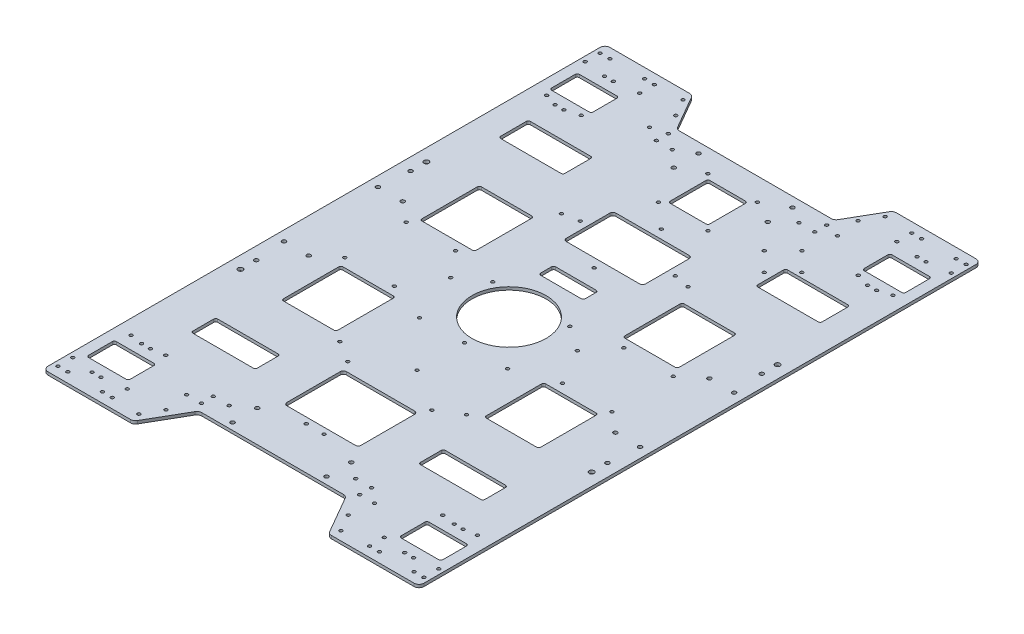
SolidWorks part; units mm, degrees
material "Hexcel AS4C (3000 丝)"
ref_plane "前视基准面" through (0, 0, 0) normal (0, 0, 1) x (1, 0, 0)
ref_plane "上视基准面" through (0, 0, 0) normal (0, 1, 0) x (1, 0, 0)
ref_plane "右视基准面" through (0, 0, 0) normal (1, 0, 0) x (0, 0, -1)
sketch "草图1" plane through (0, 0, 0) normal (0, 1, 0) x (1, 0, 0)
  line L0 (0, 420.0815) -> (0, -400.8011) construction
  line L1 (190, 287) -> (101.545, 287)
  line L2 (190, 287) -> (190, 0)
  line L3 (190, -281) -> (144.0917, -281)
  line L4 (-190, 287) -> (-190, 0)
  line L5 (-313.6361, 0) -> (397.123, 0) construction
  line L6 (144.0917, -281) -> (98.6603, -281)
  line L7 (-101.545, 287) -> (-79.6057, 249)
  line L8 (-79.6057, 249) -> (79.6057, 249)
  line L9 (79.6057, 249) -> (101.545, 287)
  line L10 (-98.6603, -281) -> (-74.4115, -239)
  line L12 (-74.4115, -239) -> (74.4115, -239)
  line L13 (-144.0917, -281) -> (-190, -281)
  line L14 (-101.545, 287) -> (-190, 287)
  line L15 (-98.6603, -281) -> (-144.0917, -281)
  line L17 (190, 0) -> (190, -281)
  line L20 (190, 287) -> (190, -281) construction
  line L22 (74.4115, -239) -> (98.6603, -281)
  line L24 (-190, 0) -> (-190, -281)
  line L26 (-190, 287) -> (-190, -281) construction
  line L44 (229.3448, 326.3448) -> (229.3448, -320.3448) construction
  line L45 (-229.3448, 326.3448) -> (-229.3448, -320.3448) construction
  line L46 (-78.8293, 326.3448) -> (-229.3448, 326.3448) construction
  line L47 (-78.8293, 326.3448) -> (-56.89, 288.3448) construction
  line L48 (-56.89, 288.3448) -> (56.89, 288.3448) construction
  line L49 (56.89, 288.3448) -> (78.8293, 326.3448) construction
  line L50 (229.3448, 326.3448) -> (78.8293, 326.3448) construction
  line L51 (-121.376, -320.3448) -> (-229.3448, -320.3448) construction
  line L52 (229.3448, -320.3448) -> (121.376, -320.3448) construction
  line L53 (-98.6603, -281) -> (-121.376, -320.3448) construction
  line L54 (98.6603, -281) -> (121.376, -320.3448) construction
  line L55 (-132.7338, -261.3276) -> (-144.0917, -281) construction
  line L56 (-132.7338, -261.3276) -> (-97.1273, -199.6552) construction
  line L57 (-97.1273, -199.6552) -> (97.1273, -199.6552) construction
  line L58 (97.1273, -199.6552) -> (132.7338, -261.3276) construction
  line L59 (132.7338, -261.3276) -> (144.0917, -281) construction
  point P0 (0, 0)
  point P10 (-110.2073, -274)
  point P13 (-79.8964, -221.5)
  point P14 (79.8964, -221.5)
  point P16 (110.2073, -274)
  point P21 (200, -271.5)
  point P22 (200, 291.5)
  point P23 (-145.7725, 287)
  point P24 (77.0076, 246.5)
  point P25 (-77.0076, 246.5)
  point P27 (-200, 291.5)
  point P28 (-200, -271.5)
  dimension "D1" = 568
  dimension "D2" = 380
  dimension "D3" = 38
  dimension "D4" = 197.3205
  dimension "D5" = 120
  dimension "D6" = 60
  dimension "D7" = 203.09
  dimension "D8" = 42
  dimension "D9" = 287
extrude "基本板" add sketch "草图1" along normal blind 3
sketch "草图2" plane through (0, 3, 0) normal (0, 1, 0) x (1, 0, 0)
  circle A0 centre (0, 0) radius 37.5
  circle A1 centre (38.9711, 22.5) radius 1.6
  circle A3 centre (0, 0) radius 37.5
  circle A5 centre (0, -45) radius 1.6
  circle A6 centre (0, 0) radius 37.5
  circle A7 centre (-38.9711, 22.5) radius 1.6
  point P14 (0, 0)
  point P16 (0, 0)
  dimension "D1" = 75
  dimension "D3" = 3.2
  dimension "D2" = 45
  dimension "D4" = 3
extrude "云台孔" cut sketch "草图2" against normal blind 3 contours A1 | A0 | A5 | A7
sketch "草图8" plane through (0, 3, 0) normal (0, 1, 0) x (1, 0, 0)
  line L0 (0, 320.5112) -> (0, -345.0597) construction
  line L13 (82.5, -149) -> (147.5, -149)
  line L14 (-82.5, -149) -> (-147.5, -149)
  line L15 (-82.5, -149) -> (-82.5, -174)
  line L16 (-82.5, -174) -> (-147.5, -174)
  line L17 (-147.5, -149) -> (-147.5, -174)
  line L18 (-82.5, -149) -> (-147.5, -174) construction
  line L19 (-82.5, -174) -> (-147.5, -149) construction
  line L20 (147.5, -149) -> (147.5, -174)
  line L21 (82.5, -149) -> (147.5, -174) construction
  line L22 (82.5, -174) -> (147.5, -149) construction
  line L23 (82.5, -149) -> (82.5, -174)
  line L24 (82.5, -174) -> (147.5, -174)
  point P12 (-115, -161.5)
  dimension "D1" = 230
  dimension "D5" = 174
  dimension "D7" = 25
  dimension "D8" = 65
extrude "减重过线孔" cut sketch "草图8" against normal blind 3
sketch "草图41" plane through (0, 3, 0) normal (0, 1, 0) x (1, 0, 0)
  line L0 (0, 188.4867) -> (0, -152.142) construction
  line L1 (-206.7892, 0) -> (229.7274, 0) construction
  line L2 (-130, 100) -> (-75, 100)
  line L3 (-130, 100) -> (-130, 40)
  line L4 (-130, 40) -> (-75, 40)
  line L5 (-75, 100) -> (-75, 40)
  line L6 (75, 100) -> (75, 40)
  line L7 (130, 40) -> (75, 40)
  line L8 (130, 100) -> (130, 40)
  line L9 (130, 100) -> (75, 100)
  line L10 (130, -100) -> (75, -100)
  line L11 (130, -100) -> (130, -40)
  line L12 (130, -40) -> (75, -40)
  line L13 (75, -100) -> (75, -40)
  line L14 (-75, -100) -> (-75, -40)
  line L15 (-130, -40) -> (-75, -40)
  line L16 (-130, -100) -> (-130, -40)
  line L17 (-130, -100) -> (-75, -100)
  dimension "D1" = 40
  dimension "D2" = 75
  dimension "D3" = 55
  dimension "D4" = 60
extrude "减重过线孔2" cut sketch "草图41" against normal blind 10
sketch "草图10" plane through (0, 3, 0) normal (0, 1, 0) x (1, 0, 0)
  line L0 (0, 320.3944) -> (0, -95.0551) construction
  line L1 (-162.5, 182) -> (-97.5, 182)
  line L2 (-162.5, 182) -> (-162.5, 152)
  line L3 (-162.5, 152) -> (-97.5, 152)
  line L4 (-97.5, 182) -> (-97.5, 152)
  line L5 (-162.5, 182) -> (-97.5, 152) construction
  line L6 (-162.5, 152) -> (-97.5, 182) construction
  line L7 (162.5, 152) -> (97.5, 152)
  line L8 (97.5, 152) -> (97.5, 182)
  line L9 (97.5, 182) -> (162.5, 182)
  line L11 (162.5, 182) -> (162.5, 152)
  point P0 (-130, 167)
  dimension "D1" = 65
  dimension "D2" = 30
  dimension "D3" = 167
  dimension "D4" = 130
  dimension "D5" = 65
extrude "后电机过线孔" cut sketch "草图10" against normal blind 3
sketch "草图11" plane through (0, 3, 0) normal (0, 1, 0) x (1, 0, 0)
  line L0 (-190, 287) -> (-190, -281) construction
  line L1 (-179, 248) -> (-137, 248)
  line L2 (-179, 248) -> (-179, 220)
  line L3 (-179, 220) -> (-137, 220)
  line L4 (-137, 248) -> (-137, 220)
  line L5 (-179, 248) -> (-137, 220) construction
  line L6 (-179, 220) -> (-137, 248) construction
  line L8 (-158, 274.32) -> (-158, 185.5546) construction
  line L9 (-208.9066, 234) -> (-106.7696, 234) construction
  line L10 (-264.4169, 0) -> (335.6364, 0) construction
  line L11 (0, 360.1922) -> (0, -386.7193) construction
  line L12 (179, 248) -> (179, 220)
  line L13 (179, 220) -> (137, 220)
  line L14 (137, 248) -> (137, 220)
  line L15 (179, 248) -> (137, 248)
  line L16 (179, -248) -> (137, -248)
  line L17 (137, -248) -> (137, -220)
  line L18 (179, -220) -> (137, -220)
  line L19 (179, -248) -> (179, -220)
  line L20 (-179, -248) -> (-179, -220)
  line L21 (-179, -220) -> (-137, -220)
  line L22 (-137, -248) -> (-137, -220)
  line L23 (-179, -248) -> (-137, -248)
  circle A0 centre (-153.5, 259) radius 1.6
  circle A1 centre (-162.5, 259) radius 1.6
  circle A2 centre (-153.5, 209) radius 1.6
  circle A3 centre (-162.5, 209) radius 1.6
  circle A4 centre (153.5, 259) radius 1.6
  circle A5 centre (162.5, 259) radius 1.6
  circle A6 centre (153.5, 209) radius 1.6
  circle A7 centre (162.5, 209) radius 1.6
  circle A8 centre (162.5, -209) radius 1.6
  circle A9 centre (153.5, -209) radius 1.6
  circle A10 centre (162.5, -259) radius 1.6
  circle A11 centre (153.5, -259) radius 1.6
  circle A12 centre (-162.5, -209) radius 1.6
  circle A13 centre (-153.5, -209) radius 1.6
  circle A14 centre (-153.5, -259) radius 1.6
  circle A15 centre (-162.5, -259) radius 1.6
  point P0 (-158, 234)
  dimension "D5" = 3.2
  dimension "D1" = 42
  dimension "D2" = 28
  dimension "D3" = 32
  dimension "D4" = 468
  dimension "D6" = 4.5
  dimension "D7" = 25
extrude "悬挂过孔" cut sketch "草图11" against normal blind 3
sketch "草图13" plane through (0, 3, 0) normal (0, 1, 0) x (1, 0, 0)
  line L0 (79.6057, 249) -> (-79.6057, 249) construction
  line L1 (25, 226) -> (-25, 226) construction
  line L2 (25, 226) -> (25, 176) construction
  line L3 (25, 176) -> (-25, 176) construction
  line L4 (-25, 226) -> (-25, 176) construction
  line L5 (25, 226) -> (-25, 176) construction
  line L6 (25, 176) -> (-25, 226) construction
  circle A0 centre (25, 176) radius 1.6
  circle A1 centre (25, 226) radius 1.6
  circle A2 centre (-25, 226) radius 1.6
  circle A3 centre (-25, 176) radius 1.6
  point P0 (0, 201)
  dimension "D1" = 3.2
  dimension "D2" = 50
  dimension "D3" = 48
  dimension "D4" = 50
extrude "原灯柱固定孔" cut sketch "草图13" against normal blind 3
sketch "草图14" plane through (0, 3, 0) normal (0, 1, 0) x (1, 0, 0)
  line L0 (0, 388.2914) -> (0, -299.2561) construction
  line L1 (79.6057, 249) -> (-79.6057, 249) construction
  line L4 (-74.4115, -239) -> (74.4115, -239) construction
  circle A0 centre (-47.5, 239) radius 2
  circle A1 centre (-47.5, 214) radius 2
  circle A2 centre (47.5, 214) radius 2
  circle A3 centre (47.5, 239) radius 2
  circle A4 centre (-47.5, -207) radius 2
  circle A5 centre (-47.5, -232) radius 2
  circle A6 centre (47.5, -232) radius 2
  circle A7 centre (47.5, -207) radius 2
  dimension "D1" = 25
  dimension "D3" = 4
  dimension "D4" = 4
  dimension "D6" = 4
  dimension "D7" = 4
  dimension "D2" = 10
  dimension "D5" = 47.5
  dimension "D8" = 25
  dimension "D9" = 7
  dimension "D10" = 95
extrude "前后装甲板固定孔" cut sketch "草图14" against normal blind 3
sketch "草图15" plane through (0, 3, 0) normal (0, 1, 0) x (1, 0, 0)
  line L0 (-212.3646, 0) -> (277.5556, 0) construction
  line L1 (190, -281) -> (190, 287) construction
  line L2 (0, 389.4336) -> (0, -385.931) construction
  circle A0 centre (155, 47.5) radius 2
  circle A1 centre (180, 47.5) radius 2
  circle A2 centre (180, -47.5) radius 2
  circle A3 centre (155, -47.5) radius 2
  circle A4 centre (-155, -47.5) radius 2
  circle A5 centre (-180, -47.5) radius 2
  circle A6 centre (-180, 47.5) radius 2
  circle A7 centre (-155, 47.5) radius 2
  dimension "D1" = 25
  dimension "D4" = 4
  dimension "D5" = 4
  dimension "D2" = 10
  dimension "D3" = 47.5
extrude "左右装甲板固定孔" cut sketch "草图15" against normal blind 3
sketch "草图16" plane through (0, 3, 0) normal (0, 1, 0) x (1, 0, 0)
  line L0 (0, 371.6115) -> (0, -351.9198) construction
  line L1 (79.6057, 249) -> (-79.6057, 249) construction
  line L2 (-74.4115, -239) -> (74.4115, -239) construction
  circle A0 centre (-64, 229) radius 1.6
  circle A1 centre (-64, 117) radius 1.6
  circle A2 centre (-64, 5) radius 1.6
  circle A3 centre (-64, -107) radius 1.6
  circle A4 centre (-64, -219) radius 1.6
  circle A5 centre (64, 229) radius 1.6
  circle A6 centre (64, -107) radius 1.6
  circle A7 centre (64, 5) radius 1.6
  circle A8 centre (64, 117) radius 1.6
  circle A9 centre (64, -219) radius 1.6
  dimension "D1" = 20
  dimension "D2" = 3.2
  dimension "D3" = 128
  dimension "D4" = 20
  dimension "D5" = 4
  dimension "D6" = 112
  dimension "D7" = 112
extrude "加强筋固定孔" cut sketch "草图16" against normal blind 3
sketch "草图17" plane through (0, 3, 0) normal (0, 1, 0) x (1, 0, 0)
  line L0 (134.2077, 331.9193) -> (53.2432, 191.6847) construction
  line L1 (101.545, 287) -> (79.6057, 249) construction
  line L2 (190, 287) -> (101.545, 287) construction
  line L3 (0, 408.349) -> (0, -455.0242) construction
  line L4 (-45.0771, -171.5407) -> (-117.5498, -297.067) construction
  line L5 (190, -281) -> (190, 287) construction
  line L6 (-190, -281) -> (-98.6603, -281) construction
  line L7 (-190, 287) -> (-190, -281) construction
  line L8 (-98.6603, -281) -> (-74.4115, -239) construction
  circle A0 centre (95, 264.0096) radius 1.6
  circle A1 centre (102.5, 277) radius 1.6
  circle A3 centre (-95, -258.0096) radius 1.6
  circle A4 centre (-102.5, -271) radius 1.6
  circle A7 centre (102.5, -271) radius 1.6
  circle A8 centre (95, -258.0096) radius 1.6
  circle A10 centre (-102.5, 277) radius 1.6
  circle A11 centre (-95, 264.0096) radius 1.6
  dimension "D2" = 15
  dimension "D4" = 3.2
  dimension "D5" = 3.2
  dimension "D6" = 95
  dimension "D11" = 3.2
  dimension "D12" = 3.2
  dimension "D3" = 95
  dimension "D8" = 10
  dimension "D14" = 10
  dimension "D16" = 15
extrude "前后挡片固定孔" [suppressed] cut sketch "草图17" against normal blind 3
sketch "草图18" plane through (0, 3, 0) normal (0, 1, 0) x (1, 0, 0)
  line L0 (325.6997, 0) -> (-414.0484, 0) construction
  line L1 (167.6795, 77.7768) -> (228.1621, 112.6965) construction
  line L2 (190, -281) -> (190, 287) construction
  line L3 (0, 334.7186) -> (0, -324.7689) construction
  line L4 (190, -281) -> (190, 287) construction
  circle A0 centre (167.6795, 77.7768) radius 1.6
  circle A1 centre (185, 87.7768) radius 1.6
  circle A2 centre (185, -87.7768) radius 1.6
  circle A3 centre (167.6795, -77.7768) radius 1.6
  circle A4 centre (-167.6795, -77.7768) radius 1.6
  circle A5 centre (-185, -87.7768) radius 1.6
  circle A6 centre (-185, 87.7768) radius 1.6
  circle A7 centre (-167.6795, 77.7768) radius 1.6
  point P24 (190, 90.6636)
  dimension "D1" = 30
  dimension "D5" = 3.2
  dimension "D6" = 3.2
  dimension "D2" = 181.3272
  dimension "D3" = 20
  dimension "D4" = 5
extrude "左右挡片固定孔" [suppressed] cut sketch "草图18" against normal blind 3
sketch "草图19" plane through (0, 3, 0) normal (0, 1, 0) x (1, 0, 0)
  line L0 (-190, 287) -> (-190, -281) construction
  line L2 (0, 300.5357) -> (0, -347.8075) construction
  line L3 (-284.3527, 0) -> (241.9977, 0) construction
  circle A0 centre (-177.5, -78) radius 2
  circle A1 centre (-177.5, -94) radius 2.5
  circle A2 centre (-177.5, 94) radius 2.5
  circle A3 centre (-177.5, 78) radius 2
  circle A4 centre (177.5, -94) radius 2.5
  circle A5 centre (177.5, -78) radius 2
  circle A6 centre (177.5, 78) radius 2
  circle A7 centre (177.5, 94) radius 2.5
  dimension "D1" = 12.5
  dimension "D3" = 4
  dimension "D4" = 5
  dimension "D2" = 188
  dimension "D5" = 16
extrude "纵车架固定孔" cut sketch "草图19" against normal blind 3
sketch "草图21" plane through (0, 3, 0) normal (0, 1, 0) x (1, 0, 0)
  line L1 (-84.0108, 0) -> (121.9234, 0) construction
  circle A0 centre (0, -93) radius 1.6
  dimension "D1" = 186
  dimension "D2" = 3.2
extrude "横车架固定孔" cut sketch "草图21" against normal blind 3
sketch "草图30" [suppressed] plane through (0, 3, 0) normal (0, 1, 0) x (1, 0, 0)
  line L0 (0, -74.9086) -> (0, -247.6971) construction
  line L1 (65, -113) -> (65, -157)
  line L2 (-77, -110) -> (-68, -110)
  line L3 (-80, -113) -> (-80, -157)
  line L4 (-77, -160) -> (-68, -160)
  line L5 (-65, -113) -> (-65, -157)
  line L6 (77, -160) -> (68, -160)
  line L7 (80, -113) -> (80, -157)
  line L8 (77, -110) -> (68, -110)
  arc A0 (-68, -110) -> (-65, -113) centre (-68, -113) cw
  arc A1 (-80, -157) -> (-77, -160) centre (-77, -157) ccw
  arc A2 (-68, -160) -> (-65, -157) centre (-68, -157) ccw
  arc A3 (-77, -110) -> (-80, -113) centre (-77, -113) ccw
  arc A4 (77, -110) -> (80, -113) centre (77, -113) cw
  arc A5 (68, -160) -> (65, -157) centre (68, -157) cw
  arc A6 (80, -157) -> (77, -160) centre (77, -157) cw
  arc A7 (68, -110) -> (65, -113) centre (68, -113) ccw
  point P11 (-65, -110)
  point P14 (-80, -160)
  point P17 (-65, -160)
  dimension "D5" = 3
  dimension "D1" = 50
  dimension "D2" = 15
  dimension "D3" = 130
  dimension "D4" = 110
sketch "草图32" plane through (0, 3, 0) normal (0, 1, 0) x (1, 0, 0)
  line L0 (0, -130.9301) -> (0, -286.8622) construction
  line L2 (-34.5, -190) -> (34.5, -190)
  line L3 (-37.5, -187) -> (-37.5, -133)
  line L4 (-34.5, -130) -> (34.5, -130)
  line L5 (37.5, -187) -> (37.5, -133)
  line L6 (0, -130) -> (0, -190) construction
  line L7 (-37.5, -160) -> (37.5, -160) construction
  arc A0 (34.5, -190) -> (37.5, -187) centre (34.5, -187) ccw
  arc A1 (-37.5, -133) -> (-34.5, -130) centre (-34.5, -133) cw
  arc A2 (-34.5, -190) -> (-37.5, -187) centre (-34.5, -187) cw
  arc A3 (34.5, -130) -> (37.5, -133) centre (34.5, -133) cw
  point P3 (0, -160)
  point P9 (37.5, -190)
  point P15 (-37.5, -130)
  point P18 (-37.5, -190)
  dimension "D4" = 3
  dimension "D1" = 60
  dimension "D2" = 75
  dimension "D3" = 160
extrude "切除-拉伸9" cut sketch "草图32" against normal blind 10
sketch "草图33" plane through (0, 3, 0) normal (0, 1, 0) x (1, 0, 0)
  line L1 (-70.5, -55) -> (70.5, -55) construction
  line L2 (-70.5, -55) -> (-70.5, -186) construction
  line L3 (-70.5, -186) -> (70.5, -186) construction
  line L4 (70.5, -55) -> (70.5, -186) construction
  line L5 (0, -186) -> (0, -55) construction
  line L6 (-70.5, -120.5) -> (70.5, -120.5) construction
  line L7 (-60, -180.5) -> (60, -180.5) construction
  line L8 (-60, -180.5) -> (-60, -60.5) construction
  line L9 (-60, -60.5) -> (60, -60.5) construction
  line L10 (60, -180.5) -> (60, -60.5) construction
  line L11 (0, -60.5) -> (0, -180.5) construction
  line L12 (-60, -120.5) -> (60, -120.5) construction
  circle A0 centre (-60, -180.5) radius 1.6 construction
  circle A1 centre (60, -180.5) radius 1.6 construction
  circle A2 centre (60, -60.5) radius 1.6 construction
  circle A3 centre (-60, -60.5) radius 1.6 construction
  circle A4 centre (-42.5, -120.5) radius 1.6
  circle A5 centre (42.5, -120.5) radius 1.6
  point P0 (0, -120.5)
  point P4 (0, -120.5)
  dimension "D6" = 3.2
  dimension "D7" = 3.2
  dimension "D8" = 3.2
  dimension "D9" = 3.2
  dimension "D10" = 3.2
  dimension "D11" = 85
  dimension "D1" = 131
  dimension "D2" = 141
  dimension "D3" = 55
  dimension "D4" = 120
  dimension "D5" = 120
extrude "PC座固定孔" cut sketch "草图33" against normal blind 10
sketch "草图36" plane through (0, 3, 0) normal (0, 1, 0) x (1, 0, 0)
  line L0 (-237.1174, 0) -> (284.0197, 0) construction
  line L1 (0, 354.7574) -> (0, -284.8649) construction
  line L2 (-74.4115, -239) -> (74.4115, -239) construction
  line L4 (79.6057, 249) -> (-79.6057, 249) construction
  circle A0 centre (-80, -231) radius 1.6
  circle A1 centre (-80, -219) radius 1.6
  circle A2 centre (80, -219) radius 1.6
  circle A3 centre (80, -231) radius 1.6
  circle A4 centre (-80, 241) radius 1.6
  circle A5 centre (-80, 229) radius 1.6
  circle A6 centre (80, 229) radius 1.6
  circle A7 centre (80, 241) radius 1.6
  dimension "D1" = 3.2
  dimension "D2" = 3.2
  dimension "D4" = 8
  dimension "D6" = 3.2
  dimension "D3" = 12
  dimension "D5" = 160
  dimension "D7" = 8
  dimension "D9" = 160
  dimension "D10" = 12
  dimension "D8" = 2
extrude "前后防撞架固定孔" cut sketch "草图36" against normal through all
sketch "草图29" plane through (0, 3, 0) normal (0, 1, 0) x (1, 0, 0)
  line L1 (40, 98) -> (40, 142)
  line L2 (37, 95) -> (-37, 95)
  line L3 (-40, 98) -> (-40, 142)
  line L4 (37, 145) -> (-37, 145)
  line L5 (-40, 120) -> (40, 120) construction
  line L6 (0, 95) -> (0, 145) construction
  arc A0 (40, 142) -> (37, 145) centre (37, 142) ccw
  arc A1 (-37, 95) -> (-40, 98) centre (-37, 98) cw
  arc A2 (40, 98) -> (37, 95) centre (37, 98) cw
  arc A3 (-40, 142) -> (-37, 145) centre (-37, 142) cw
  circle A4 centre (48, 120) radius 1.6
  circle A5 centre (0, 86) radius 1.6
  circle A6 centre (0, 154) radius 1.6
  circle A7 centre (-48, 120) radius 1.6
  point P0 (0, 120)
  point P6 (40, 145)
  point P12 (-40, 95)
  point P15 (40, 95)
  dimension "D4" = 3
  dimension "D5" = 3.2
  dimension "D7" = 3.2
  dimension "D8" = 68
  dimension "D1" = 80
  dimension "D2" = 50
  dimension "D3" = 120
  dimension "D6" = 96
extrude "电池座固定孔" cut sketch "草图29" against normal blind 10
sketch "草图39" plane through (0, 3, 0) normal (0, 1, 0) x (1, 0, 0)
  line L0 (185, -224.8149) -> (185, -286) construction
  line L1 (190, -281) -> (190, 287) construction
  line L2 (130, -286) -> (185, -286) construction
  line L3 (98.6603, -281) -> (190, -281) construction
  line L4 (130, -224.8149) -> (130, -286) construction
  line L5 (0, -68.0168) -> (0, -303.6758) construction
  line L6 (-288.2309, 3) -> (310.1394, 3) construction
  line L7 (130, 230.8149) -> (130, 292) construction
  line L8 (130, 292) -> (185, 292) construction
  line L9 (185, 230.8149) -> (185, 292) construction
  line L10 (190, 287) -> (101.545, 287) construction
  line L11 (157.5, -286) -> (157.5, -234.7139) construction
  circle A0 centre (185, -271) radius 1.6
  circle A1 centre (185, -256) radius 1.6
  circle A2 centre (130, -256) radius 1.6
  circle A3 centre (130, -271) radius 1.6
  circle A4 centre (-130, -271) radius 1.6
  circle A5 centre (-130, -256) radius 1.6
  circle A6 centre (-185, -256) radius 1.6
  circle A7 centre (-185, -271) radius 1.6
  circle A8 centre (-130, 262) radius 1.6
  circle A9 centre (-130, 277) radius 1.6
  circle A10 centre (185, 262) radius 1.6
  circle A11 centre (185, 277) radius 1.6
  circle A12 centre (-185, 277) radius 1.6
  circle A13 centre (-185, 262) radius 1.6
  circle A14 centre (130, 277) radius 1.6
  circle A15 centre (130, 262) radius 1.6
  dimension "D3" = 3.2
  dimension "D4" = 15
  dimension "D5" = 15
  dimension "D8" = 5
  dimension "D1" = 5
  dimension "D2" = 5
  dimension "D6" = 55
extrude "对角防撞架固定孔" cut sketch "草图39" against normal blind 10
sketch "草图42" plane through (0, 3, 0) normal (0, 1, 0) x (1, 0, 0)
  line L0 (-25, 226) -> (25, 176) construction
  line L1 (-25, 176) -> (25, 226) construction
  line L3 (-20, 221) -> (20, 221)
  line L4 (-20, 221) -> (-20, 181)
  line L5 (-20, 181) -> (20, 181)
  line L6 (20, 221) -> (20, 181)
  line L7 (0, 181) -> (0, 221) construction
  line L8 (-20, 201) -> (20, 201) construction
  point P8 (0, 201)
  dimension "D1" = 40
extrude "切除-拉伸11" cut sketch "草图42" against normal blind 10
sketch "草图43" plane through (0, 3, 0) normal (0, 1, 0) x (1, 0, 0)
  line L0 (0, 69.935) -> (0, -77.0754) construction
  line L1 (-56.3274, 0) -> (63.1225, 0) construction
  line L32 (75, 32.5) -> (75, -32.5) construction
  line L33 (81, 32.5) -> (81, -32.5)
  line L34 (69, 32.5) -> (69, -32.5)
  line L35 (95, 32.5) -> (95, -32.5) construction
  line L36 (101, 32.5) -> (101, -32.5)
  line L37 (89, 32.5) -> (89, -32.5)
  line L38 (115, 32.5) -> (115, -32.5) construction
  line L39 (121, 32.5) -> (121, -32.5)
  line L40 (109, 32.5) -> (109, -32.5)
  line L41 (135, 32.5) -> (135, -32.5) construction
  line L42 (141, 32.5) -> (141, -32.5)
  line L43 (129, 32.5) -> (129, -32.5)
  line L44 (-75, 32.5) -> (-75, -32.5) construction
  line L45 (-81, 32.5) -> (-81, -32.5)
  line L46 (-69, 32.5) -> (-69, -32.5)
  line L47 (-95, 32.5) -> (-95, -32.5) construction
  line L48 (-101, 32.5) -> (-101, -32.5)
  line L49 (-89, 32.5) -> (-89, -32.5)
  line L50 (-115, 32.5) -> (-115, -32.5) construction
  line L51 (-121, 32.5) -> (-121, -32.5)
  line L52 (-109, 32.5) -> (-109, -32.5)
  line L53 (-135, 32.5) -> (-135, -32.5) construction
  line L54 (-141, 32.5) -> (-141, -32.5)
  line L55 (-129, 32.5) -> (-129, -32.5)
  arc A0 (81, 32.5) -> (69, 32.5) centre (75, 32.5) ccw
  arc A1 (69, -32.5) -> (81, -32.5) centre (75, -32.5) ccw
  arc A5 (101, 32.5) -> (89, 32.5) centre (95, 32.5) ccw
  arc A6 (89, -32.5) -> (101, -32.5) centre (95, -32.5) ccw
  arc A7 (121, 32.5) -> (109, 32.5) centre (115, 32.5) ccw
  arc A8 (109, -32.5) -> (121, -32.5) centre (115, -32.5) ccw
  arc A9 (141, 32.5) -> (129, 32.5) centre (135, 32.5) ccw
  arc A10 (129, -32.5) -> (141, -32.5) centre (135, -32.5) ccw
  arc A11 (-81, 32.5) -> (-69, 32.5) centre (-75, 32.5) cw
  arc A12 (-69, -32.5) -> (-81, -32.5) centre (-75, -32.5) cw
  arc A13 (-101, 32.5) -> (-89, 32.5) centre (-95, 32.5) cw
  arc A14 (-89, -32.5) -> (-101, -32.5) centre (-95, -32.5) cw
  arc A15 (-121, 32.5) -> (-109, 32.5) centre (-115, 32.5) cw
  arc A16 (-109, -32.5) -> (-121, -32.5) centre (-115, -32.5) cw
  arc A17 (-141, 32.5) -> (-129, 32.5) centre (-135, 32.5) cw
  arc A18 (-129, -32.5) -> (-141, -32.5) centre (-135, -32.5) cw
  point P4 (75, 0)
  point P16 (95, 0)
  point P23 (115, 0)
  point P30 (135, 0)
  point P35 (-75, 0)
  point P42 (-95, 0)
  point P49 (-115, 0)
  point P57 (-135, 0)
  dimension "D1" = 4
  dimension "D4" = 75
  dimension "D5" = 20
  dimension "D2" = 12
  dimension "D3" = 65
extrude "切除-拉伸12" [suppressed] cut sketch "草图43" against normal blind 10
sketch "草图44" [suppressed] plane through (0, 3, 0) normal (0, 1, 0) x (1, 0, 0)
  line L0 (0, 99.1729) -> (0, -37.5) construction
  circle A0 centre (115, -264) radius 1.6
  circle A3 centre (185, -264) radius 1.6 construction
  circle A4 centre (185, -264) radius 1.6
  circle A5 centre (0, 0) radius 37.5 construction
  circle A6 centre (185, -231) radius 1.6
  circle A7 centre (185, 284) radius 1.6 construction
  circle A8 centre (185, 284) radius 1.6
  circle A9 centre (-115, -264) radius 1.6
  circle A10 centre (-185, -231) radius 1.6
  circle A11 centre (115, 284) radius 1.6
  circle A12 centre (185, 241) radius 1.6
  circle A13 centre (-185, 241) radius 1.6
  circle A14 centre (-115, 284) radius 1.6
  point P15 (0, 30.8364)
  dimension "D1" = 3.2
  dimension "D3" = 3.2
  dimension "D5" = 3.2
  dimension "D6" = 3.2
  dimension "D2" = 70
  dimension "D4" = 33
  dimension "D7" = 43
  dimension "D8" = 70
extrude "切除-拉伸13" [suppressed] cut sketch "草图44" against normal through all
sketch "草图34" plane through (0, 3, 0) normal (0, 1, 0) x (1, 0, 0)
  line L1 (71, 206) -> (109, 206) construction
  line L2 (71, 206) -> (71, 168) construction
  line L3 (71, 168) -> (109, 168) construction
  line L4 (109, 206) -> (109, 168) construction
  line L5 (90, 168) -> (90, 206) construction
  line L6 (71, 187) -> (109, 187) construction
  circle A0 centre (90, 168) radius 1.6
  circle A1 centre (71, 187) radius 1.6
  circle A2 centre (90, 206) radius 1.6
  circle A3 centre (109, 187) radius 1.6
  point P0 (90, 187)
  dimension "D2" = 3.2
  dimension "D3" = 3.2
  dimension "D4" = 3.2
  dimension "D7" = 3.2
  dimension "D1" = 38
  dimension "D5" = 90
  dimension "D6" = 187
extrude "UWB固定孔" cut sketch "草图34" against normal blind 10
sketch "草图47" plane through (0, 3, 0) normal (0, 1, 0) x (1, 0, 0)
  line L0 (0, 349.8553) -> (0, -296.5751) construction
  circle A0 centre (140, 277) radius 1.6
  circle A1 centre (185, -271) radius 1.6 construction
  circle A2 centre (185, -271) radius 1.6
  circle A3 centre (95, -231) radius 1.6
  circle A4 centre (175, -271) radius 1.6
  circle A5 centre (140, 213) radius 1.6
  circle A6 centre (175, -207) radius 1.6
  circle A7 centre (-140, -271) radius 1.6
  circle A8 centre (-140, -207) radius 1.6
  circle A9 centre (-175, 213) radius 1.6
  circle A10 centre (-95, 237) radius 1.6
  circle A11 centre (185, 277) radius 1.6 construction
  circle A12 centre (185, 277) radius 1.6
  circle A13 centre (175, 277) radius 1.6
  circle A14 centre (95, 237) radius 1.6
  circle A15 centre (175, 213) radius 1.6
  circle A16 centre (-175, 277) radius 1.6
  circle A17 centre (-185, 277) radius 1.6
  circle A18 centre (140, -207) radius 1.6
  circle A19 centre (140, -271) radius 1.6
  circle A20 centre (-175, -207) radius 1.6
  circle A21 centre (-140, 213) radius 1.6
  circle A22 centre (-175, -271) radius 1.6
  circle A23 centre (-95, -231) radius 1.6
  circle A24 centre (-185, -271) radius 1.6
  circle A25 centre (-140, 277) radius 1.6
  dimension "D3" = 3.2
  dimension "D6" = 3.2
  dimension "D8" = 64
  dimension "D10" = 3.2
  dimension "D13" = 3.2
  dimension "D2" = 3.2
  dimension "D9" = 3.2
  dimension "D16" = 2
  dimension "D19" = 35
  dimension "D4" = 80
  dimension "D5" = 40
  dimension "D7" = 64
  dimension "D11" = 40
  dimension "D12" = 80
  dimension "D14" = 10
  dimension "D15" = 10
  dimension "D17" = 35
  dimension "D18" = 2
extrude "救援固定孔" cut sketch "草图47" against normal through all
sketch "草图48" plane through (0, 3, 0) normal (0, 1, 0) x (1, 0, 0)
  line L0 (0, 63.9696) -> (0, -155.8034) construction
  circle A0 centre (-44.5, -46) radius 1.6
  circle A1 centre (44.5, -46) radius 1.6
  circle A2 centre (-9, -196) radius 1.6
  circle A3 centre (9, -196) radius 1.6
  dimension "D3" = 3.2
  dimension "D6" = 3.2
  dimension "D1" = 44.5
  dimension "D2" = 46
  dimension "D4" = 9
  dimension "D5" = 196
extrude "切除-拉伸14" cut sketch "草图48" against normal through all
sketch "草图50" plane through (0, 0, 0) normal (0, -1, 0) x (1, 0, 0)
  circle A0 centre (-99.3301, -275.8397) radius 1.5 construction
  circle A1 centre (-91.8301, -262.8494) radius 1.5 construction
  circle A2 centre (99.3301, -275.8397) radius 1.5 construction
  circle A3 centre (91.8301, -262.8494) radius 1.5 construction
  circle A4 centre (-99.3301, 269.8397) radius 1.5 construction
  circle A5 centre (-91.8301, 256.8494) radius 1.5 construction
  circle A6 centre (91.8301, 256.8494) radius 1.5 construction
  circle A7 centre (99.3301, 269.8397) radius 1.5 construction
  circle A8 centre (-99.3301, -275.8397) radius 1.5
  circle A9 centre (-91.8301, -262.8494) radius 1.5
  circle A10 centre (99.3301, -275.8397) radius 1.5
  circle A11 centre (91.8301, -262.8494) radius 1.5
  circle A12 centre (-99.3301, 269.8397) radius 1.5
  circle A13 centre (-91.8301, 256.8494) radius 1.5
  circle A14 centre (91.8301, 256.8494) radius 1.5
  circle A15 centre (99.3301, 269.8397) radius 1.5
extrude "切除-拉伸16" [suppressed] cut sketch "草图50" against normal blind 10
sketch "草图51" plane through (0, 3, 0) normal (0, 1, 0) x (1, 0, 0)
  line L0 (0, -15.6528) -> (0, -161.3511) construction
  line L2 (-20.5, 67.5) -> (20.5, 67.5)
  line L3 (-22.5, 65.5) -> (-22.5, 54.5)
  line L4 (-20.5, 52.5) -> (20.5, 52.5)
  line L5 (22.5, 65.5) -> (22.5, 54.5)
  line L6 (0, 52.5) -> (0, 67.5) construction
  line L7 (-22.5, 60) -> (22.5, 60) construction
  arc A0 (20.5, 67.5) -> (22.5, 65.5) centre (20.5, 65.5) cw
  arc A1 (-22.5, 54.5) -> (-20.5, 52.5) centre (-20.5, 54.5) ccw
  arc A2 (-20.5, 67.5) -> (-22.5, 65.5) centre (-20.5, 65.5) ccw
  arc A3 (20.5, 52.5) -> (22.5, 54.5) centre (20.5, 54.5) ccw
  point P3 (0, 60)
  point P9 (22.5, 67.5)
  point P15 (-22.5, 52.5)
  point P18 (-22.5, 67.5)
  dimension "D4" = 2
  dimension "D5" = 2
  dimension "D6" = 2
  dimension "D7" = 2
  dimension "D1" = 15
  dimension "D2" = 45
  dimension "D3" = 60
extrude "6623电机过线孔" cut sketch "草图51" against normal blind 10
fillet "外圆角" radius 5 12 edges at (-190, 1.5, -287) (-101.545, 1.5, -287) (-79.6057, 1.5, -249) (79.6057, 1.5, -249) (101.545, 1.5, -287) (190, 1.5, -287) (190, 1.5, 281) (98.6603, 1.5, 281) (74.4115, 1.5, 239) (-74.4115, 1.5, 239) (-98.6603, 1.5, 281) (-190, 1.5, 281)
fillet "内圆角" radius 2 52 edges at (-147.5, 1.5, 149) (-82.5, 1.5, 149) (-82.5, 1.5, 174) (-147.5, 1.5, 174) (82.5, 1.5, 149) (147.5, 1.5, 149) (147.5, 1.5, 174) (82.5, 1.5, 174) (-130, 1.5, -100) (-75, 1.5, -100) (-75, 1.5, -40) (-130, 1.5, -40) (-130, 1.5, 100) (-130, 1.5, 40) (-75, 1.5, 40) (-75, 1.5, 100) (130, 1.5, 100) (75, 1.5, 100) (75, 1.5, 40) (130, 1.5, 40) (130, 1.5, -100) (130, 1.5, -40) (75, 1.5, -40) (75, 1.5, -100) (-97.5, 1.5, -152) (-162.5, 1.5, -152) (-162.5, 1.5, -182) (-97.5, 1.5, -182) (162.5, 1.5, -182) (-137, 1.5, -220) (-179, 1.5, -220) (-179, 1.5, -248) (-137, 1.5, -248) (-179, 1.5, 220) (-137, 1.5, 220) (-137, 1.5, 248) (179, 1.5, 248) (137, 1.5, 248) (137, 1.5, 220) (179, 1.5, 220) (179, 1.5, -248) (179, 1.5, -220) (137, 1.5, -220) (137, 1.5, -248) (20, 1.5, -181) (-20, 1.5, -181) (-20, 1.5, -221) (20, 1.5, -221) (-179, 1.5, 248) (162.5, 1.5, -152) (97.5, 1.5, -152) (97.5, 1.5, -182)
sketch "草图52" plane through (0, 3, 0) normal (0, 1, 0) x (1, 0, 0)
  line L0 (0, 174.243) -> (0, -94.6) construction
  line L1 (80, 190) -> (80, 208) construction
  line L2 (-125.2, 190) -> (-80, 190) construction
  line L3 (-125.2, 190) -> (-125.2, 208) construction
  line L4 (-125.2, 208) -> (-80, 208) construction
  line L5 (-80, 190) -> (-80, 208) construction
  line L6 (125.2, 208) -> (80, 208) construction
  line L7 (125.2, 190) -> (125.2, 208) construction
  line L8 (125.2, 190) -> (80, 190) construction
  line L13 (-85, -130) -> (-130.2, -130) construction
  line L14 (85, -121) -> (130.2, -121) construction
  line L15 (85, -121) -> (85, -139) construction
  line L16 (85, -139) -> (130.2, -139) construction
  line L17 (130.2, -121) -> (130.2, -139) construction
  line L18 (107.6, -139) -> (107.6, -121) construction
  line L19 (85, -130) -> (130.2, -130) construction
  line L20 (-107.6, -139) -> (-107.6, -121) construction
  line L21 (-130.2, -121) -> (-130.2, -139) construction
  line L22 (-85, -139) -> (-130.2, -139) construction
  line L23 (-85, -121) -> (-85, -139) construction
  line L24 (-85, -121) -> (-130.2, -121) construction
  circle A0 centre (-125.2, 190) radius 1.6
  circle A1 centre (-80, 190) radius 1.6
  circle A2 centre (-80, 208) radius 1.6
  circle A3 centre (-125.2, 208) radius 1.6
  circle A4 centre (125.2, 208) radius 1.6
  circle A5 centre (80, 208) radius 1.6
  circle A6 centre (80, 190) radius 1.6
  circle A7 centre (125.2, 190) radius 1.6
  circle A9 centre (85, -139) radius 1.6
  circle A10 centre (130.2, -139) radius 1.6
  circle A11 centre (130.2, -121) radius 1.6
  circle A12 centre (85, -121) radius 1.6
  circle A13 centre (-85, -121) radius 1.6
  circle A14 centre (-130.2, -121) radius 1.6
  circle A15 centre (-130.2, -139) radius 1.6
  circle A16 centre (-85, -139) radius 1.6
  circle A17 centre (0, -93) radius 1.6 construction
  point P29 (107.6, -130)
  point P55 (-106.25, -130)
  dimension "D3" = 2
  dimension "D10" = 3.2
  dimension "D4" = 2
  dimension "D2" = 3.2
  dimension "D6" = 2
  dimension "D7" = 45.2
  dimension "D8" = 18
  dimension "D9" = 45.2
  dimension "D13" = 2
  dimension "D11" = 170
  dimension "D12" = 130
  dimension "D14" = 80
  dimension "D5" = 18
  dimension "D15" = 190
extrude "3508电调固定孔" [suppressed] cut sketch "草图52" against normal blind 10
sketch "草图53" plane through (0, 3, 0) normal (0, 1, 0) x (1, 0, 0)
  line L0 (0, -84.1974) -> (0, 49.8195) construction
  line L1 (-135, 31) -> (-85, 31) construction
  line L2 (-135, 31) -> (-135, -31) construction
  line L3 (-135, -31) -> (-85, -31) construction
  line L4 (-85, 31) -> (-85, -31) construction
  line L5 (-110, -31) -> (-110, 31) construction
  line L6 (-135, 0) -> (-85, 0) construction
  line L7 (135, 0) -> (85, 0) construction
  line L8 (110, -31) -> (110, 31) construction
  line L9 (85, 31) -> (85, -31) construction
  line L10 (135, -31) -> (85, -31) construction
  line L11 (135, 31) -> (135, -31) construction
  line L12 (135, 31) -> (85, 31) construction
  circle A0 centre (-135, -31) radius 1.6
  circle A1 centre (-85, -31) radius 1.6
  circle A2 centre (-85, 31) radius 1.6
  circle A3 centre (-135, 31) radius 1.6
  circle A4 centre (135, 31) radius 1.6
  circle A5 centre (85, 31) radius 1.6
  circle A6 centre (85, -31) radius 1.6
  circle A7 centre (135, -31) radius 1.6
  point P0 (-110, 0)
  point P26 (110, 0)
  dimension "D3" = 3.2
  dimension "D1" = 62
  dimension "D2" = 50
  dimension "D4" = 110
extrude "RFID固定孔" cut sketch "草图53" against normal blind 10
sketch "草图54" plane through (0, 0, 0) normal (0, -1, 0) x (1, 0, 0)
  line L0 (-263.9822, -3) -> (389.5678, -3) construction
  line L1 (0, -107.2403) -> (0, -312.9663) construction
  line L2 (-102.1224, -278) -> (-92.1224, -260.6795) construction
  line L3 (-81.0491, -251.5) -> (-100.1016, -284.5) construction
  line L4 (-104.4318, -287) -> (-185, -287) construction
  line L5 (102.1224, -278) -> (92.1224, -260.6795) construction
  line L6 (102.1224, 272) -> (92.1224, 254.6795) construction
  line L7 (-102.1224, 272) -> (-92.1224, 254.6795) construction
  line L8 (-185, 281) -> (-101.547, 281) construction
  circle A0 centre (-102.1224, -278) radius 1.6
  circle A1 centre (-92.1224, -260.6795) radius 1.6
  circle A2 centre (92.1224, -260.6795) radius 1.6
  circle A3 centre (102.1224, -278) radius 1.6
  circle A4 centre (102.1224, 272) radius 1.6
  circle A5 centre (92.1224, 254.6795) radius 1.6
  circle A6 centre (-92.1224, 254.6795) radius 1.6
  circle A7 centre (-102.1224, 272) radius 1.6
  dimension "D1" = 3.2
  dimension "D2" = 3.2
  dimension "D3" = 5
  dimension "D4" = 9
  dimension "D5" = 20
  dimension "D6" = 9
extrude "挡片固定孔" cut sketch "草图54" against normal blind 10
